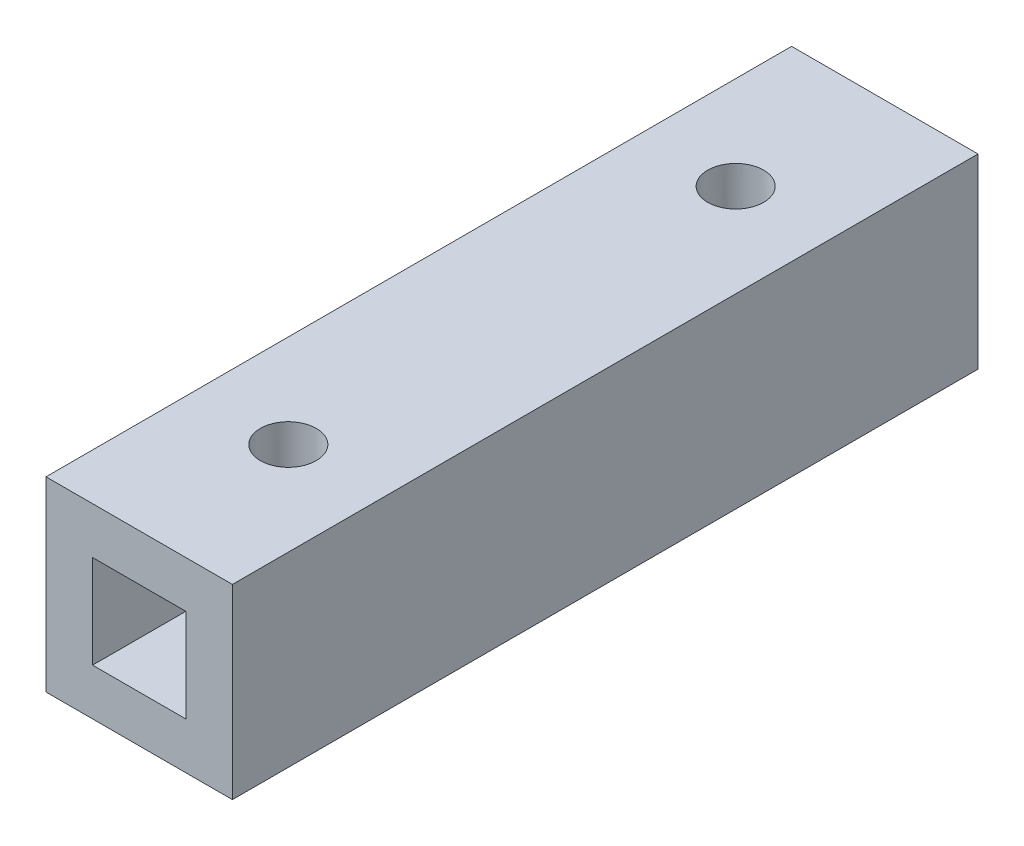
SolidWorks part; units mm, degrees
ref_plane "前视基准面" through (0, 0, 0) normal (0, 0, 1) x (1, 0, 0)
ref_plane "上视基准面" through (0, 0, 0) normal (0, 1, 0) x (1, 0, 0)
ref_plane "右视基准面" through (0, 0, 0) normal (1, 0, 0) x (0, 0, -1)
sketch "草图1" plane through (0, 0, 0) normal (0, 0, 1) x (1, 0, 0)
  line L1 (-5, -5) -> (5, -5)
  line L2 (-5, -5) -> (-5, 5)
  line L3 (-5, 5) -> (5, 5)
  line L4 (5, -5) -> (5, 5)
  line L5 (-5, -5) -> (5, 5) construction
  line L6 (-5, 5) -> (5, -5) construction
  point P0 (0, 0)
  dimension "D1" = 10
  dimension "D2" = 10
extrude "凸台-拉伸1" add sketch "草图1" along normal blind 40
sketch "草图2" plane through (0, 5, 0) normal (0, 1, 0) x (1, 0, 0)
  line L0 (5, 0) -> (-5, 0) construction
  circle A0 centre (0, -8) radius 1.5
  dimension "D1" = 3
  dimension "D2" = 8
extrude "切除-拉伸1" cut sketch "草图2" against normal through all both and the other way through all
sketch "草图3" plane through (0, 5, 0) normal (0, 1, 0) x (1, 0, 0)
  line L0 (0, -40) -> (0, -32.9423) construction
  line L1 (5, -40) -> (-5, -40) construction
  circle A0 centre (0, -32) radius 1.5
  dimension "D1" = 3
  dimension "D2" = 8
extrude "切除-拉伸2" cut sketch "草图3" against normal through all both and the other way through all
sketch "草图4" plane through (0, 0, 40) normal (0, 0, 1) x (1, 0, 0)
  line L0 (5, 5) -> (-5, 5) construction
  line L1 (-2.5, 2.5) -> (2.5, 2.5)
  line L2 (-2.5, 2.5) -> (-2.5, -2.5)
  line L3 (-2.5, -2.5) -> (2.5, -2.5)
  line L4 (2.5, 2.5) -> (2.5, -2.5)
  line L5 (-2.5, 2.5) -> (2.5, -2.5) construction
  line L6 (-2.5, -2.5) -> (2.5, 2.5) construction
  line L7 (5, -5) -> (5, 5) construction
  point P0 (0, 0)
  dimension "D1" = 2.5
  dimension "D2" = 2.5
extrude "切除-拉伸3" cut sketch "草图4" against normal through all both
